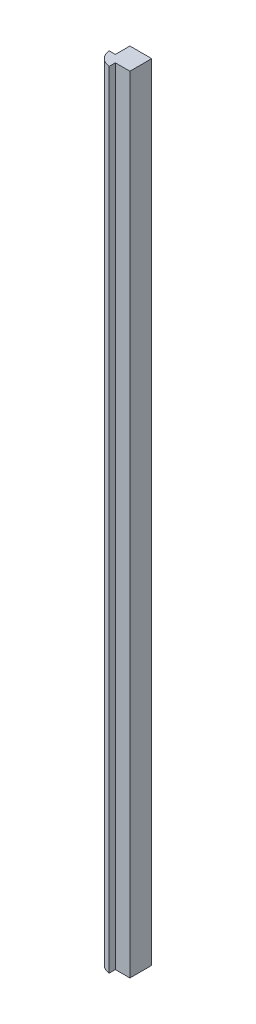
SolidWorks part; units mm, degrees
material "Free-Cutting Brass, UNS C36000"
ref_plane "Front Plane" through (0, 0, 0) normal (0, 0, 1) x (1, 0, 0)
ref_plane "Top Plane" through (0, 0, 0) normal (0, 1, 0) x (1, 0, 0)
ref_plane "Right Plane" through (0, 0, 0) normal (1, 0, 0) x (0, 0, -1)
sketch "Sketch1" plane through (0, 0, 0) normal (0, 1, 0) x (1, 0, 0)
  line L3 (3.175, 12.7) -> (12.7, 12.7)
  line L4 (12.7, 3.175) -> (12.7, 12.7)
  line L7 (12.7, 3.175) -> (6.35, 3.175)
  line L8 (6.35, 0.508) -> (6.35, 3.175)
  line L11 (0.508, 6.35) -> (3.175, 6.35)
  line L12 (3.175, 12.7) -> (3.175, 6.35)
  arc A0 (0.508, 6.35) -> (6.35, 0.508) centre (6.8391, 6.8391) ccw
  point P7 (0, 0)
  dimension "D3" = 6.35
  dimension "D1" = 12.7
  dimension "D2" = 12.7
  dimension "D4" = 6.35
  dimension "D5" = 6.35
  dimension "D6" = 2.667
  dimension "D7" = 2.667
  dimension "D8" = 9.525
  dimension "D9" = 9.525
extrude "Boss-Extrude1" add sketch "Sketch1" along normal blind 342.9
